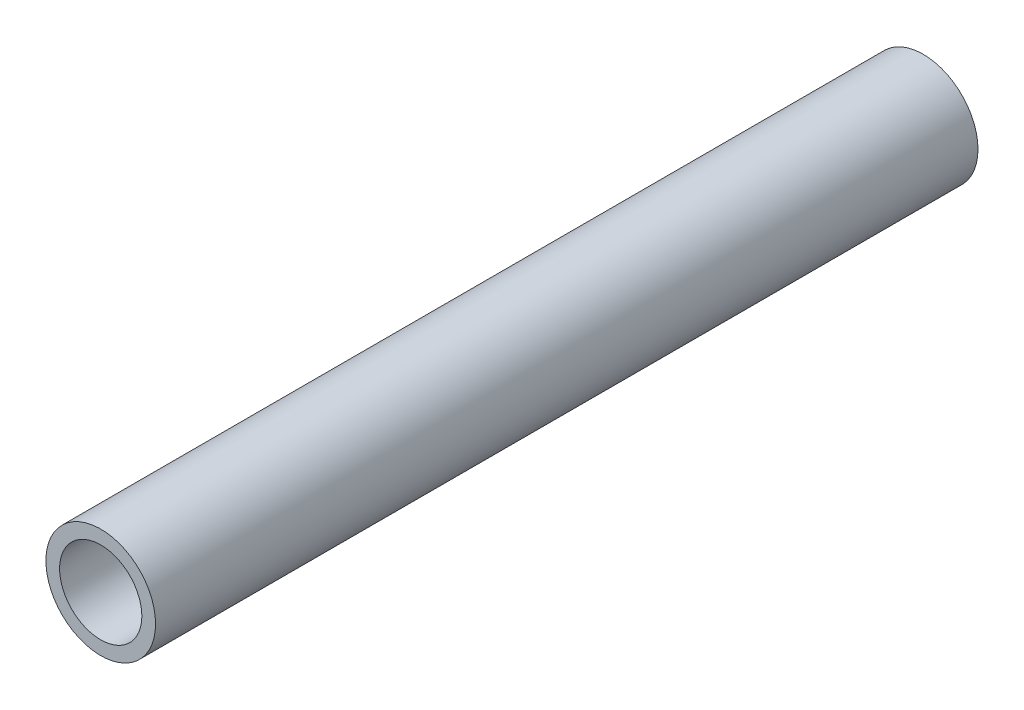
SolidWorks part; units mm, degrees
ref_plane "Front Plane" through (0, 0, 0) normal (0, 0, 1) x (1, 0, 0)
ref_plane "Top Plane" through (0, 0, 0) normal (0, 1, 0) x (1, 0, 0)
ref_plane "Right Plane" through (0, 0, 0) normal (1, 0, 0) x (0, 0, -1)
sketch "Sketch1" plane through (0, 0, 0) normal (0, 0, 1) x (1, 0, 0)
  circle A0 centre (0, 0) radius 9.525
  circle A1 centre (0, 0) radius 12.7
  dimension "D1" = 19.05
  dimension "D2" = 25.4
extrude "Boss-Extrude1" add sketch "Sketch1" along normal blind 190.5
